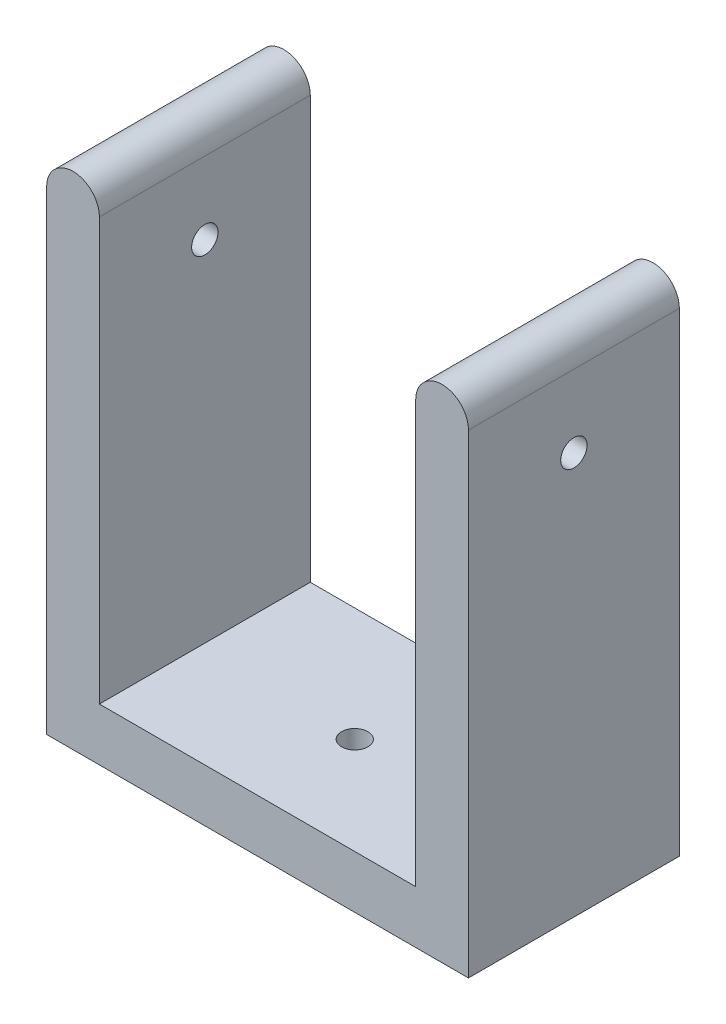
SolidWorks part; units mm, degrees
ref_plane "Front Plane" through (0, 0, 0) normal (0, 0, 1) x (1, 0, 0)
ref_plane "Top Plane" through (0, 0, 0) normal (0, 1, 0) x (1, 0, 0)
ref_plane "Right Plane" through (0, 0, 0) normal (1, 0, 0) x (0, 0, -1)
sketch "Sketch2" plane through (0, 0, 0) normal (0, 0, 1) x (1, 0, 0)
  line L0 (-20, 0) -> (20, 0)
  line L1 (20, 0) -> (20, 45)
  line L3 (15, 45) -> (15, 5)
  line L4 (15, 5) -> (-15, 5)
  line L5 (-15, 5) -> (-15, 45)
  line L7 (-20, 45) -> (-20, 0)
  arc A0 (-20, 45) -> (-15, 45) centre (-17.5, 45) cw
  arc A1 (15, 45) -> (20, 45) centre (17.5, 45) cw
  point P4 (0, 0)
  dimension "D1" = 40
  dimension "D2" = 45
  dimension "D3" = 5
  dimension "D4" = 5
extrude "Boss-Extrude3" add sketch "Sketch2" along normal blind 20
sketch "Sketch3" plane through (-20, 0, 0) normal (-1, 0, 0) x (0, 0, 1)
  line L0 (20, 45) -> (20, 0) construction
  circle A0 centre (10, 38.1377) radius 1.25
  dimension "D1" = 10
extrude "Cut-Extrude1" cut sketch "Sketch3" against normal through all
sketch "Sketch5" plane through (0, 0, 0) normal (0, -1, 0) x (1, 0, 0)
  line L0 (20, 20) -> (20, 0) construction
  circle A0 centre (0, 10.7831) radius 1.25
  point P4 (0, 0)
  dimension "D1" = 20
extrude "Cut-Extrude2" cut sketch "Sketch5" against normal through all
